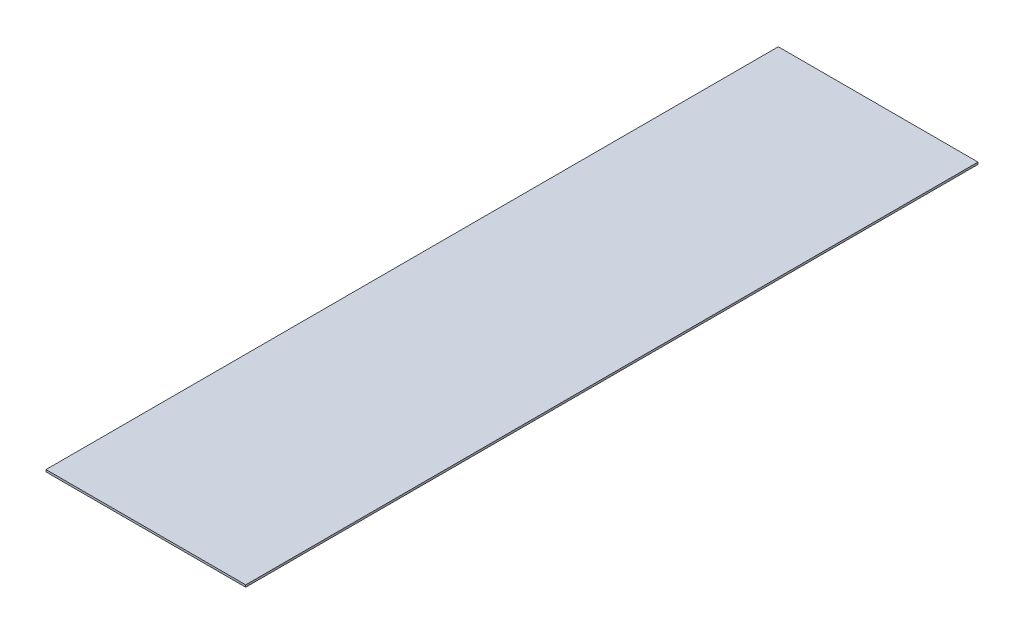
SolidWorks part; units mm, degrees
material "Delrin 2700 NC010, Low Viscosity Acetal Copolymer (SS)"
ref_plane "Front Plane" through (0, 0, 0) normal (0, 0, 1) x (1, 0, 0)
ref_plane "Top Plane" through (0, 0, 0) normal (0, 1, 0) x (1, 0, 0)
ref_plane "Right Plane" through (0, 0, 0) normal (1, 0, 0) x (0, 0, -1)
sketch "Sketch1" plane through (0, 0, 0) normal (0, 1, 0) x (1, 0, 0)
  line L0 (-38.1, 139.7) -> (38.1, -139.7) construction
  line L1 (-38.1, 139.7) -> (38.1, 139.7)
  line L2 (-38.1, 139.7) -> (-38.1, -139.7)
  line L3 (-38.1, -139.7) -> (38.1, -139.7)
  line L4 (38.1, 139.7) -> (38.1, -139.7)
  point P4 (0, 0)
extrude "Boss-Extrude1" add sketch "Sketch1" along normal blind 0.7937
